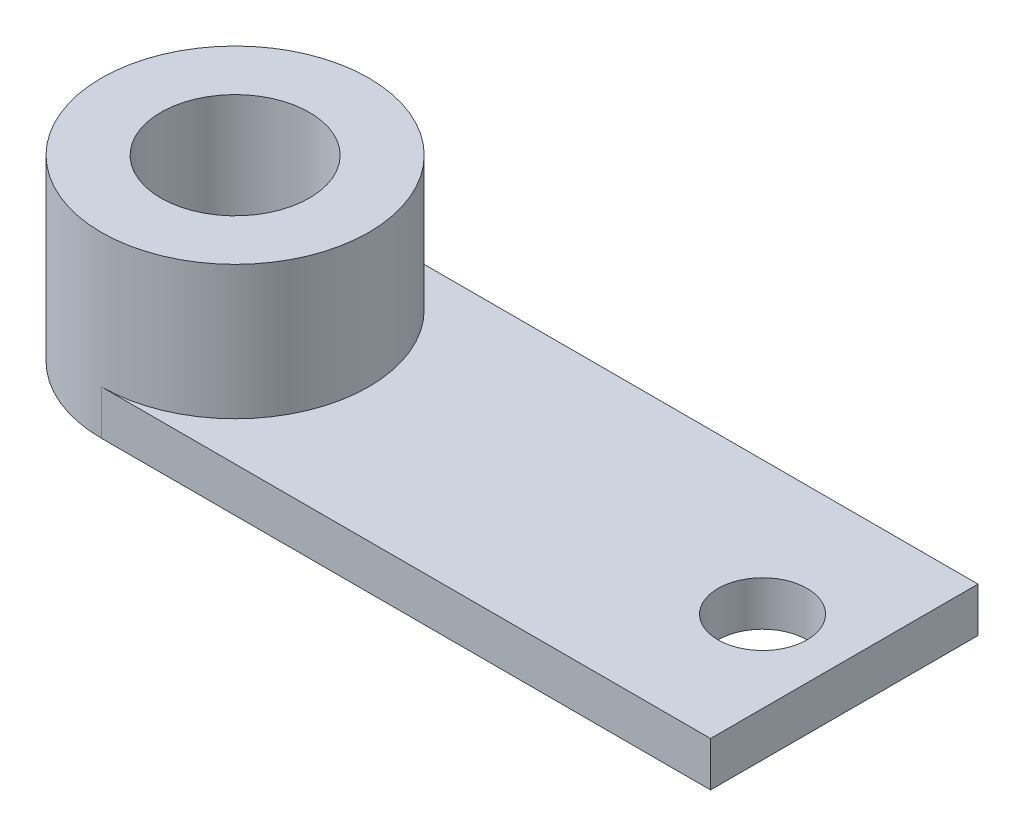
SolidWorks part; units mm, degrees
ref_plane "Front Plane" through (0, 0, 0) normal (0, 0, 1) x (1, 0, 0)
ref_plane "Top Plane" through (0, 0, 0) normal (0, 1, 0) x (1, 0, 0)
ref_plane "Right Plane" through (0, 0, 0) normal (1, 0, 0) x (0, 0, -1)
sketch "Sketch2" plane through (0, 0, 0) normal (0, 1, 0) x (1, 0, 0)
  line L0 (0, 0) -> (25, 0)
  line L1 (25, 0) -> (25, 9)
  line L2 (25, 9) -> (0, 9)
  line L3 (0, 9) -> (0, 0)
  line L4 (0, 4.5) -> (4.5, 4.5) construction
  line L5 (25, 4.5) -> (22.25, 4.5) construction
  dimension "D1" = 25
  dimension "D2" = 9
  dimension "D3" = 4.5
  dimension "D5" = 2.75
extrude "Boss-Extrude3" add sketch "Sketch2" along normal blind 6
sketch "Sketch3" plane through (0, 6, 0) normal (0, 1, 0) x (1, 0, 0)
  line L0 (0, 4.5) -> (4.5, 4.5) construction
  line L1 (0, 9) -> (0, 0) construction
  line L2 (25, 4.5) -> (22.25, 4.5) construction
  line L3 (25, 0) -> (25, 9) construction
  circle A0 centre (4.5, 4.5) radius 2.5
  circle A1 centre (22.25, 4.5) radius 1.75
  dimension "D3" = 5
  dimension "D4" = 3.5
  dimension "D1" = 4.5
  dimension "D2" = 2.75
extrude "Cut-Extrude1" cut sketch "Sketch3" against normal blind 4.5 contours A0
sketch "Sketch4" plane through (0, 6, 0) normal (0, 1, 0) x (1, 0, 0)
  line L0 (25, 4.5) -> (22.25, 4.5) construction
  line L1 (25, 0) -> (25, 9) construction
  circle A0 centre (22.25, 4.5) radius 1.5
  dimension "D2" = 3
  dimension "D1" = 2.75
extrude "Cut-Extrude2" cut sketch "Sketch4" against normal through all both and the other way through all
sketch "Sketch5" plane through (0, 6, 0) normal (0, 1, 0) x (1, 0, 0)
  line L0 (4.5, 9) -> (0, 9)
  line L1 (0, 9) -> (0, 4.5)
  line L2 (0, 4.5) -> (0, 0)
  line L3 (0, 0) -> (4.5, 0)
  line L4 (4.5, 0) -> (25, 0)
  line L5 (25, 0) -> (25, 9)
  line L6 (25, 9) -> (4.5, 9)
  circle A0 centre (4.5, 4.5) radius 4.5
  circle M9 centre (22.25, 4.5) radius 1.5
  line M12 (0, 0) -> (25, 0)
  line M13 (25, 0) -> (25, 9)
  line M14 (25, 9) -> (0, 9)
extrude "Cut-Extrude3" cut sketch "Sketch5" against normal blind 4.5 contours A0 M12 M13 M14 M9
sketch "Sketch6" plane through (0, 6, 0) normal (0, 1, 0) x (1, 0, 0)
  line L0 (4.5, 9) -> (0, 9)
  line L1 (0, 9) -> (0, 0)
  line L2 (0, 0) -> (4.5, 0)
  circle A0 centre (4.5, 4.5) radius 4.5
  line M2 (0, 0) -> (4.5, 0)
  line M4 (4.5, 9) -> (0, 9)
  line M5 (0, 9) -> (0, 0)
extrude "Cut-Extrude4" cut sketch "Sketch6" against normal through all contours A0 M4 M5 | A0 L1 M2
